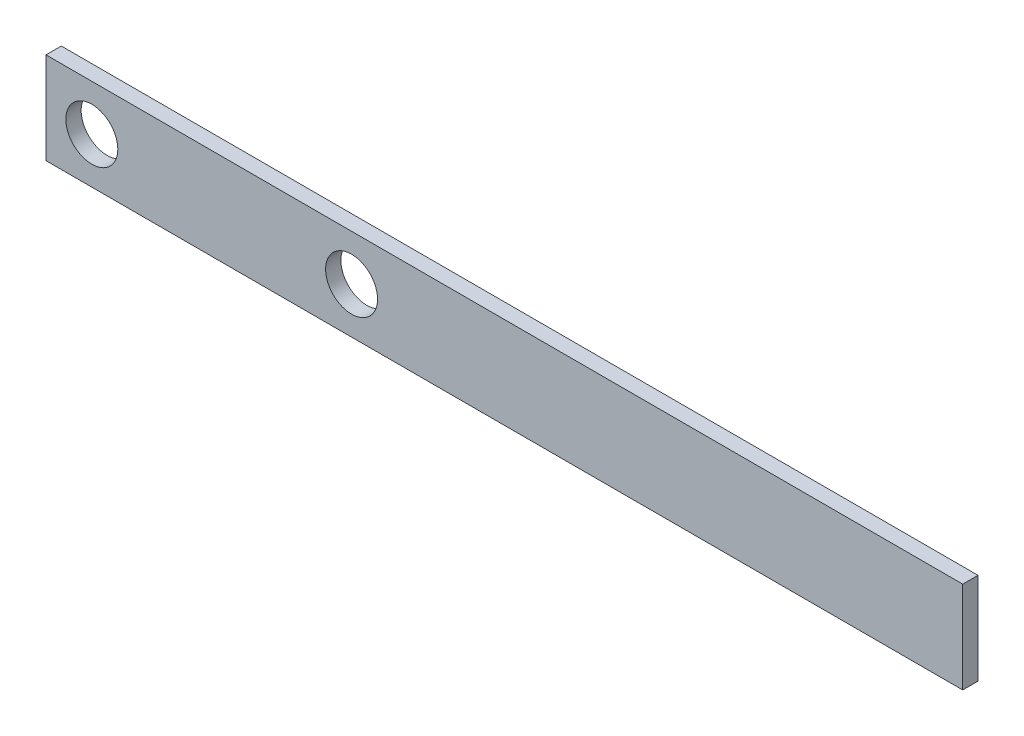
SolidWorks part; units mm, degrees
material "6061 Alloy"
ref_plane "Front Plane" through (0, 0, 0) normal (0, 0, 1) x (1, 0, 0)
ref_plane "Top Plane" through (0, 0, 0) normal (0, 1, 0) x (1, 0, 0)
ref_plane "Right Plane" through (0, 0, 0) normal (1, 0, 0) x (0, 0, -1)
sketch "Sketch1" plane through (0, 0, 0) normal (0, 0, 1) x (1, 0, 0)
  line L1 (30, -3) -> (-30, -3)
  line L2 (30, -3) -> (30, 3)
  line L3 (30, 3) -> (-30, 3)
  line L4 (-30, -3) -> (-30, 3)
  line L5 (30, -3) -> (-30, 3) construction
  line L6 (30, 3) -> (-30, -3) construction
  point P0 (0, 0)
  dimension "D1" = 60
  dimension "D2" = 6
extrude "Boss-Extrude1" add sketch "Sketch1" along normal blind 1
hole_wizard "M3 Clearance Hole1" positions "Sketch2" profile "Sketch3" hole size "M3" standard "GB" end condition through all
sketch "Sketch2" plane through (0, 0, 1) normal (0, 0, 1) x (1, 0, 0)
  line L0 (-30, 3) -> (-30, -3) construction
  point P0 (-27, 0)
  point P2 (-10, 0)
  dimension "D1" = 17
  dimension "D2" = 3
sketch "Sketch3" plane through (-27, 0, 1) normal (1, 0, 0) x (0, -1, 0)
  line L0 (0, 0) -> (0, 1)
  line L1 (0, 1) -> (1.7, 1)
  line L2 (1.7, 1) -> (1.7, 0)
  line L5 (1.7, 0) -> (0, 0)
  line L11 (0, -6.35) -> (0, 107.95) construction
  dimension "Thru Hole Dia." = 3.4
  dimension "Thru Hole Depth" = 1
